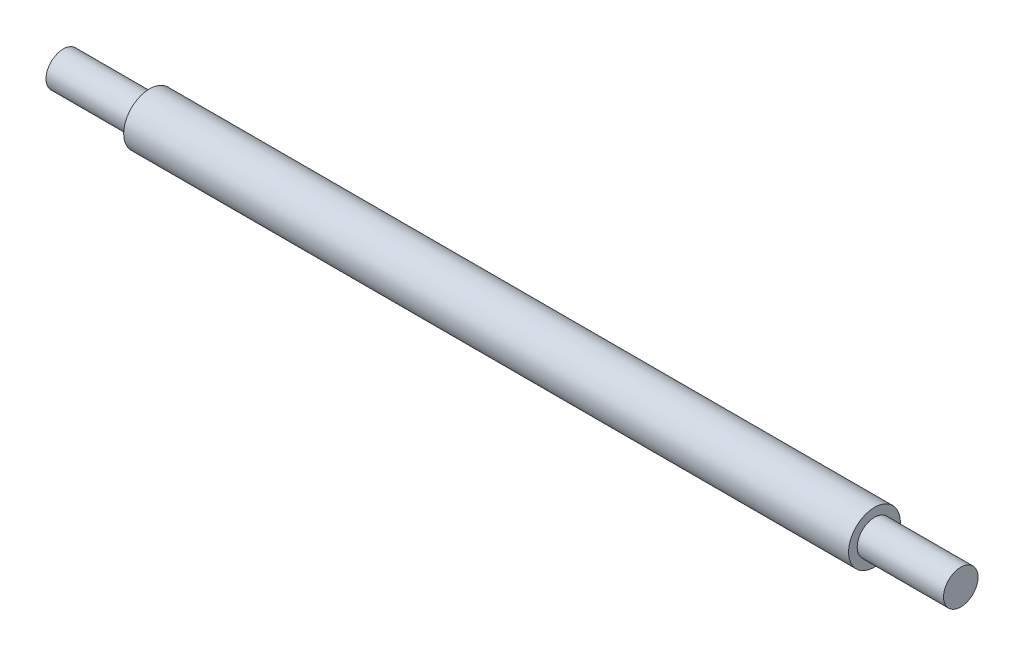
SolidWorks part; units mm, degrees
ref_plane "Front Plane" through (0, 0, 0) normal (0, 0, 1) x (1, 0, 0)
ref_plane "Top Plane" through (0, 0, 0) normal (0, 1, 0) x (1, 0, 0)
ref_plane "Right Plane" through (0, 0, 0) normal (1, 0, 0) x (0, 0, -1)
sketch "Sketch1" plane through (0, 0, 0) normal (0, 1, 0) x (1, 0, 0)
  line L0 (0, 0) -> (0, 8506.7103) construction
  line L1 (0, 0) -> (8506.7103, 0) construction
  line L2 (52, 0) -> (52, 2)
  line L3 (52, 2) -> (42, 2)
  line L4 (42, 2) -> (42, 3)
  line L5 (42, 3) -> (-42, 3)
  line L6 (-42, 3) -> (-42, 2)
  line L7 (-42, 2) -> (-52, 2)
  line L8 (-52, 2) -> (-52, 0)
  line L9 (-52, 0) -> (52, 0)
  point P13 (52, 1)
  dimension "D1" = 6
  dimension "D2" = 4
  dimension "D3" = 104
  dimension "D4" = 10
revolve "Revolve1" add sketch "Sketch1" angle 360 about L1
